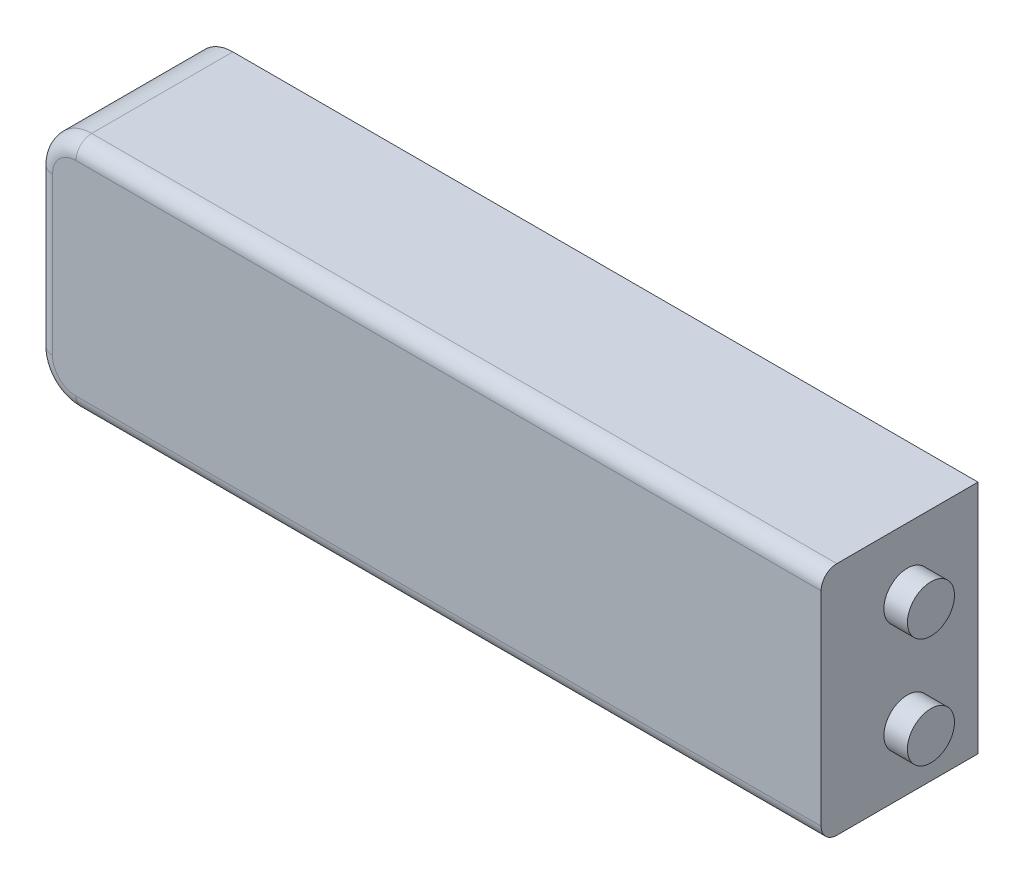
SolidWorks part; units mm, degrees
ref_plane "Front Plane" through (0, 0, 0) normal (0, 0, 1) x (1, 0, 0)
ref_plane "Top Plane" through (0, 0, 0) normal (0, 1, 0) x (1, 0, 0)
ref_plane "Right Plane" through (0, 0, 0) normal (1, 0, 0) x (0, 0, -1)
sketch "Sketch1" plane through (0, 0, 0) normal (0, 0, 1) x (1, 0, 0)
  line L1 (0, 0) -> (-95, 0)
  line L2 (0, 0) -> (0, 30)
  line L3 (0, 30) -> (-95, 30)
  line L4 (-100, 5) -> (-100, 25)
  arc A0 (-95, 0) -> (-100, 5) centre (-95, 5) cw
  arc A1 (-95, 30) -> (-100, 25) centre (-95, 25) ccw
  point P7 (-100, 0)
  point P10 (-100, 30)
  dimension "D3" = 5
  dimension "D1" = 100
  dimension "D2" = 30
extrude "Boss-Extrude1" add sketch "Sketch1" along normal blind 20
sketch "Sketch3" plane through (0, 0, 0) normal (1, 0, 0) x (0, 0, -1)
  line L0 (-20, 30) -> (0, 30) construction
  line L1 (-20, 0) -> (0, 0) construction
  line L2 (0, 0) -> (0, 30) construction
  circle A0 centre (-9, 22) radius 3
  circle A1 centre (-9, 8) radius 3
  point P8 (0, 0)
  dimension "D1" = 6
  dimension "D2" = 6
  dimension "D3" = 8
  dimension "D4" = 8
  dimension "D5" = 9
extrude "Boss-Extrude3" add sketch "Sketch3" along normal blind 3 contours A0 | A1
fillet "Fillet2" radius 2 5 edges at (-47.5, 0, 20) (-98.5355, 1.4645, 20) (-100, 15, 20) (-98.5355, 28.5355, 20) (-47.5, 30, 20)
